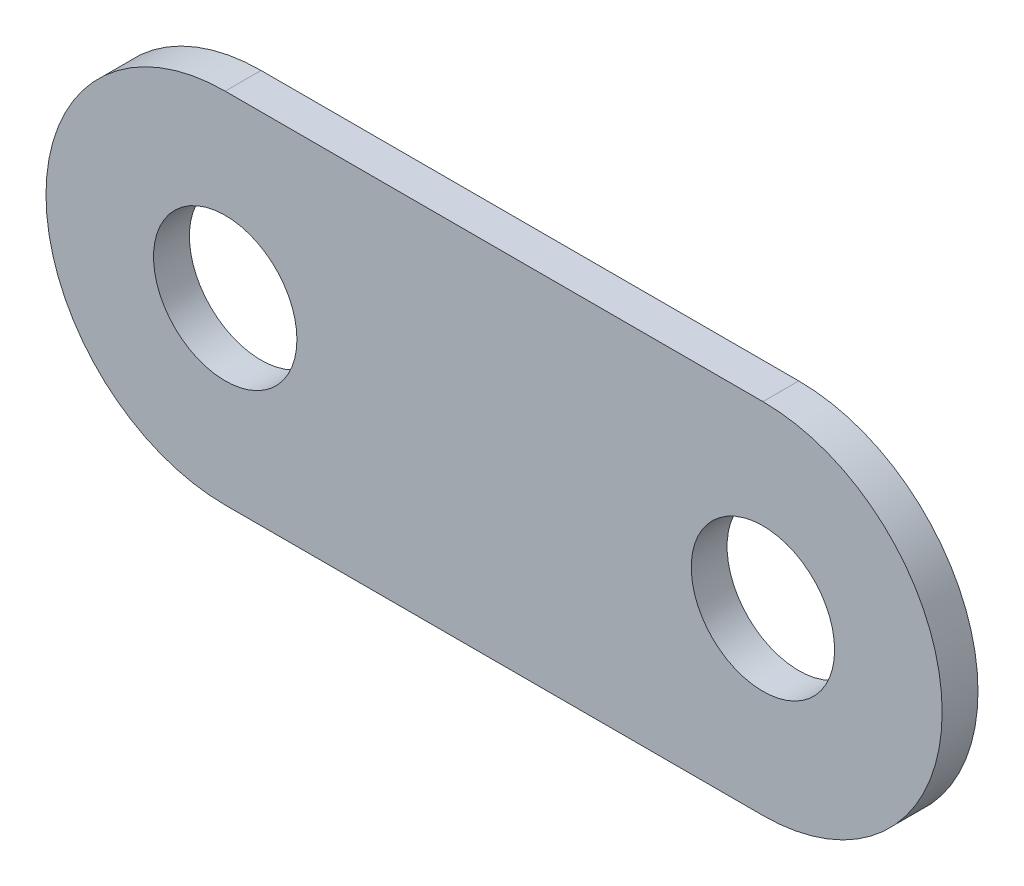
SolidWorks part; units mm, degrees
ref_plane "Спереди" through (0, 0, 0) normal (0, 0, 1) x (1, 0, 0)
ref_plane "Сверху" through (0, 0, 0) normal (0, 1, 0) x (1, 0, 0)
ref_plane "Справа" through (0, 0, 0) normal (1, 0, 0) x (0, 0, -1)
sketch "Эскиз1" plane through (0, 0, 0) normal (0, 0, 1) x (1, 0, 0)
  line L0 (5, 0) -> (20, 0)
  line L1 (20, -10) -> (5, -10)
  arc A0 (20, 0) -> (25, -5) centre (20, -5) cw
  arc A1 (25, -5) -> (20, -10) centre (20, -5) cw
  arc A2 (5, -10) -> (0, -5) centre (5, -5) cw
  arc A3 (5, 0) -> (0, -5) centre (5, -5) ccw
  circle A4 centre (5, -5) radius 2
  circle A5 centre (20, -5) radius 2
  point P3 (25, -5)
  point P4 (0, -5)
extrude "Бобышка-Вытянуть1" add sketch "Эскиз1" along normal blind 1
